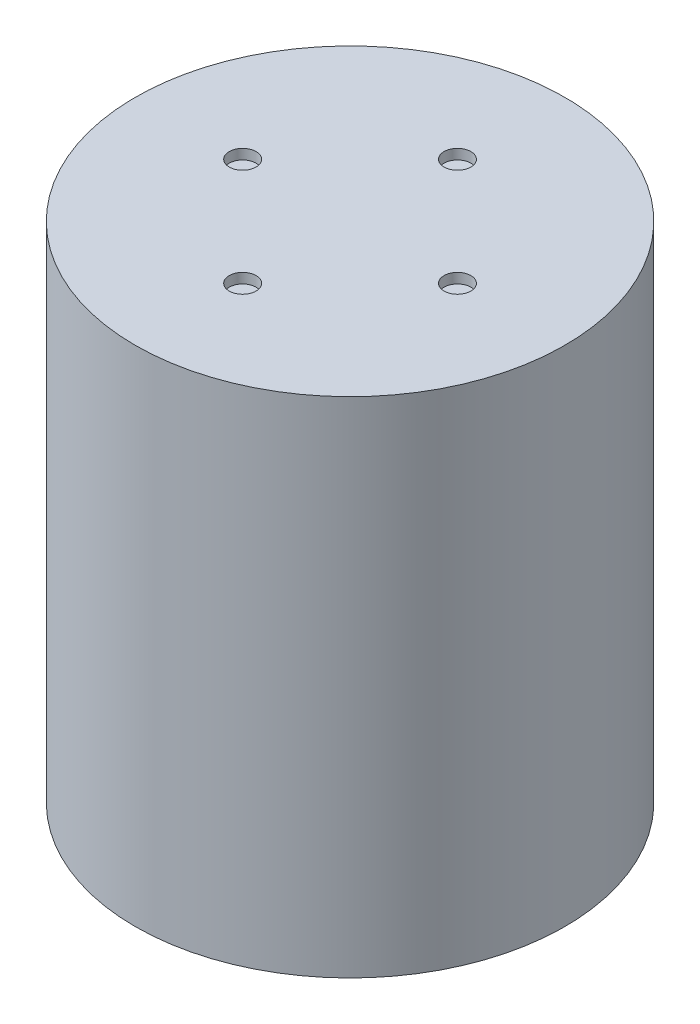
SolidWorks part; units mm, degrees
ref_plane "Front Plane" through (0, 0, 0) normal (0, 0, 1) x (1, 0, 0)
ref_plane "Top Plane" through (0, 0, 0) normal (0, 1, 0) x (1, 0, 0)
ref_plane "Right Plane" through (0, 0, 0) normal (1, 0, 0) x (0, 0, -1)
sketch "Sketch1" plane through (0, 0, 0) normal (0, 1, 0) x (1, 0, 0)
  circle A0 centre (0, 0) radius 32
  dimension "D1" = 64
extrude "Boss-Extrude1" add sketch "Sketch1" along normal blind 75
sketch "Sketch2" plane through (0, 0, 0) normal (0, -1, 0) x (1, 0, 0)
  circle A0 centre (0, 0) radius 22 construction
  circle A1 centre (0, 22) radius 2
  circle A2 centre (22, 0) radius 2
  circle A3 centre (0, -22) radius 2
  circle A4 centre (-22, 0) radius 2
  point P14 (0, 0)
  dimension "D1" = 44
  dimension "D2" = 4
  dimension "D3" = 4
extrude "Cut-Extrude1" cut sketch "Sketch2" against normal blind 1.5
sketch "Sketch3" plane through (0, 0, 0) normal (0, -1, 0) x (1, 0, 0)
  line L0 (0, 0) -> (0, 22) construction
  line L1 (0, 22) -> (22, 0) construction
  line L2 (22, 0) -> (0, 0) construction
  line L3 (0, 0) -> (15.5563, 15.5563) construction
  line L4 (12.7279, 18.3848) -> (18.3848, 12.7279) construction
  line L5 (14.1421, 19.799) -> (19.799, 14.1421) construction
  line L6 (11.3137, 16.9706) -> (16.9706, 11.3137) construction
  line L7 (13.435, 19.0919) -> (19.0919, 13.435)
  line L8 (12.0208, 17.6777) -> (17.6777, 12.0208)
  arc A0 (14.1421, 19.799) -> (11.3137, 16.9706) centre (12.7279, 18.3848) ccw construction
  arc A1 (16.9706, 11.3137) -> (19.799, 14.1421) centre (18.3848, 12.7279) ccw construction
  arc A2 (17.6777, 12.0208) -> (19.0919, 13.435) centre (18.3848, 12.7279) ccw
  arc A3 (13.435, 19.0919) -> (12.0208, 17.6777) centre (12.7279, 18.3848) ccw
  point P9 (15.5563, 15.5563)
  dimension "D3" = 2
  dimension "D1" = 22
  dimension "D2" = 8
  dimension "D4" = 1
extrude "Boss-Extrude2" add sketch "Sketch3" along normal blind 6
sketch "Sketch4" plane through (0, 75, 0) normal (0, 1, 0) x (1, 0, 0)
  circle A0 centre (0, 0) radius 16 construction
  circle A1 centre (0, 16) radius 2
  circle A2 centre (16, 0) radius 2
  circle A3 centre (0, -16) radius 2
  circle A4 centre (-16, 0) radius 2
  point P14 (0, 0)
  dimension "D2" = 4
  dimension "D3" = 4
  dimension "D1" = 32
extrude "Cut-Extrude2" cut sketch "Sketch4" against normal blind 1.5
equation "\"Np_b\"= 33"
equation "\"module\"= 0.6"
equation "\"pressure angle\"= 20.0"
equation "\"h_a\"= 0.6"
equation "\"h_b\"= 0.75"
equation "\"clr_tip_root\"= 0.15000000000000002"
equation "\"fw_p_s\"= 24.345791438896047"
equation "\"Nr\"= 78"
equation "\"pressure_angle\"= 20.0"
equation "\"h_f\"= 0.75"
equation "\"dp_r\"= 46.8"
equation "\"db_r\"= 43.97761465278051"
equation "\"fw_r\"= 22.845791438896047"
equation "\"alpha_r\"= 0.8539582918412556"
equation "\"beta_r\"= 4.015608891374819"
equation "\"bearing_ID\"= 45"
equation "\"bearing_OD\"= 58"
equation "\"bearing_height\"= 7"
equation "\"clearance_planet\"= 1.5"
equation "\"case_dist\"= 24.210783717444997"
equation "\"Motor_case_OD_max\"= 88.5"
equation "\"case_mounting_PCD\"= 81.0"
equation "\"bearing mount thickness\"= IIF((\"bearing_OD\" + \"output_mounting_hole_dia\" * 4) > (\"Nr\" * \"module\" + 2 * \"h_b\"), \"output_mounting_hole_dia\" * 2, ((\"Nr\" * \"module\" + 2 * \"h_b\" - (\"bearing_OD\" + \"output_mounting_hole_dia\" * 4)) / 2) + \"output_mounting_hole_dia\" * 2 + \"standard_clearance_1_5mm\")"
equation "\"case_mounting_hole_dia\"= 3"
equation "\"output_mounting_PCD\"= 66"
equation "\"output_mounting_hole_dia\"= 4"
equation "\"clearance_case_mount_holes_shell_thickness\"= 1"
equation "\"motor_case_OD_base\"= 79.0"
equation "\"sec_carrier_thickness\"= 5"
equation "\"sun_coupler_hub_thickness\"= 4"
equation "\"clearance_sun_coupler_sec_carrier\"= 1.5"
equation "\"clearance_motor_and_case\"= 5"
equation "\"motor_OD\"= 64"
equation "\"Motor_case_thickness\"= 2.5"
equation "\"Motor_case_ID\"= 74"
equation "\"case_mounting_hole_shift\"= 1.0"
equation "\"output_mounting_nut_wrench_size\"= 7"
equation "\"output_mounting_nut_thickness\"= 3.2"
equation "\"case_mounting_hole_allen_socket_dia\"= 5.5"
equation "\"output_mounting_nut_depth\"= 3"
equation "\"case_mounting_bolt_depth\"= 4.5"
equation "\"Ns\"= 24"
equation "\"ring_radial_thickness\"= 7.100000000000001"
equation "\"ring_OD\"= 61.0"
equation "\"ring_to_chamfer_clearance\"= 0.5"
equation "\"Motor_case_OD_base_to_chamfer\"= 5"
equation "\"pattern_offset_from_motor_case_OD_base\"= 3"
equation "\"pattern_bulge_dia\"= 3"
equation "\"pattern_num_bulge\"= 18"
equation "\"pattern_depth\"= 2"
equation "\"motor_height\"= 75"
equation "\"case_mounting_wrench_size\"= 5.5"
equation "\"case_mounting_nut_clearance\"= 2"
equation "\"base_plate_thickness\"= 4"
equation "\"case_mounting_nut_thickness\"= 2.4"
equation "\"case_mounting_surface_height\"= 4"
equation "\"motor_mount_hole_PCD\"= 44"
equation "\"motor_mount_hole_dia\"= 4"
equation "\"motor_mount_hole_num\"= 4"
equation "\"central_hole_offset_from_motor_mount_PCD\"= 5"
equation "\"wire_slot_dist_from_center\"= 22"
equation "\"wire_slot_length\"= 8"
equation "\"wire_slot_radius\"= 2"
equation "\"driver_upper_holes_dist_from_center\"= 29"
equation "\"driver_lower_holes_dist_from_center\"= 13"
equation "\"driver_side_holes_dist_from_center\"= 22.5"
equation "\"driver_mount_holes_dia\"= 3"
equation "\"driver_mount_inserts_OD\"= 4.8"
equation "\"driver_mount_thickness\"= 1.5"
equation "\"driver_mount_height\"= 6"
equation "\"air_flow_hole_offset\"= 3"
equation "\"num_planet\"= 3"
equation "\"planet_pin_bolt_dia\"= 2.5"
equation "\"planet_pin_socket_head_dia\"= 4.5"
equation "\"carrier_PCD\"= 34.199999999999996"
equation "\"planet_shaft_dia\"= 5"
equation "\"planet_shaft_step_offset\"= 0.8"
equation "\"carrier_trapezoidal_support_sun_offset\"= 5"
equation "\"carrier_trapezoidal_support_hole_PCD_offset_bearing_ID\"= 4"
equation "\"carrier_trapezoidal_support_hole_dia\"= 3"
equation "\"carrier_trapezoidal_support_hole_socket_head_dia\"= 5.5"
equation "\"carrier_bearing_step_width\"= 1.5"
equation "\"standard_clearance_1_5mm\"= 1.5"
equation "\"standard_fillet_1_5mm\"= 1.5"
equation "\"sun_shaft_bearing_OD\"= 14"
equation "\"sun_shaft_bearing_width\"= 5"
equation "\"standard_bearing_insertion_chamfer\"= 0.5"
equation "\"carrier_trapezoidal_support_hole_wrench_size\"= 5.5"
equation "\"planet_pin_bolt_wrench_size\"= 5"
equation "\"planet_bearing_OD\"= 8"
equation "\"planet_bearing_width\"= 2.5"
equation "\"planet_bore\"= 6"
equation "\"D1@Boss-Extrude1\"=\"motor_height\""
equation "\"D1@Sketch1\"=\"motor_OD\""
equation "\"D1@Sketch2\"=\"motor_mount_hole_PCD\""
equation "\"D2@Sketch2\"=\"motor_mount_hole_dia\""
equation "\"D3@Sketch2\"=\"motor_mount_hole_num\""
equation "\"D1@Cut-Extrude1\"=\"standard_clearance_1_5mm\""
equation "\"D1@Sketch3\"=\"wire_slot_dist_from_center\""
equation "\"D2@Sketch3\"=\"wire_slot_length\""
equation "\"D3@Sketch3\"=\"wire_slot_radius\""
equation "\"D1@Boss-Extrude2\"=\"standard_clearance_1_5mm\"*4"
equation "\"motor_output_hole_PCD\"= 32"
equation "\"motor_output_hole_dia\"= 4"
equation "\"motor_output_hole_num\"= 4"
equation "\"D1@Sketch4\"=\"motor_output_hole_PCD\""
equation "\"D2@Sketch4\"=\"motor_output_hole_dia\""
equation "\"D3@Sketch4\"=\"motor_output_hole_num\""
equation "\"D1@Cut-Extrude2\"=\"standard_clearance_1_5mm\""
equation "\"dp_s\"= 14.399999999999999"
equation "\"db_s\"= 13.53157373931708"
equation "\"fw_s_calc\"= 16.210783717444997"
equation "\"alpha_s\"= 0.8539582918412343"
equation "\"beta_s\"= 5.792083416317531"
equation "\"dp_p_b\"= 19.8"
equation "\"db_p_b\"= 18.605913891560988"
equation "\"alpha_p_b\"= 0.8539582918412414"
equation "\"beta_p_b\"= 3.7466288708629714"
equation "\"sun_shaft_bearing_ID\"= 7"
equation "\"sun_hub_dia\"= 42.0"
equation "\"sun_central_bolt_dia\"= 3"
equation "\"sun_central_bolt_socket_head_dia\"= 5.5"
equation "\"fw_s_used\"= 48.55657515634104"
equation "\"motor_output_hole_CSK_OD\"= 8"
equation "\"motor_output_hole_CSK_head_height\"= 2.0"
equation "\"bearing_retainer_thickness\"= 2"
equation "\"Np_s\"= 21"
equation "\"fw_p_b\"= 16.210783717444997"
equation "\"dp_p_s\"= 12.6"
equation "\"db_p_s\"= 11.840127021902445"
equation "\"alpha_p_s\"= 0.8539582918412556"
equation "\"beta_p_s\"= 6.86351198774606"
